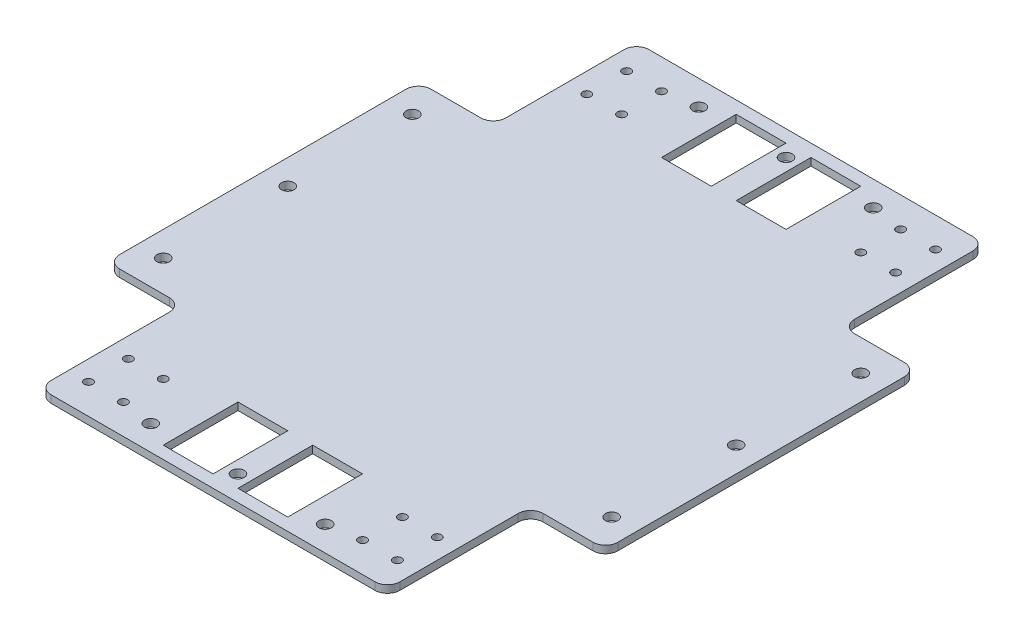
SolidWorks part; units mm, degrees
ref_plane "前视基准面" through (0, 0, 0) normal (0, 0, 1) x (1, 0, 0)
ref_plane "上视基准面" through (0, 0, 0) normal (0, 1, 0) x (1, 0, 0)
ref_plane "右视基准面" through (0, 0, 0) normal (1, 0, 0) x (0, 0, -1)
other "Configuration Table"
sketch "草图1" plane through (0, 0, 0) normal (0, 1, 0) x (1, 0, 0)
  line L0 (0, 120) -> (0, -49880) construction
  line L5 (-100, -120) -> (100, 120) construction
  line L6 (-100, 120) -> (100, -120) construction
  line L7 (-100, 120) -> (-70, 120)
  line L8 (-100, 120) -> (-100, 80)
  line L9 (-95, 80) -> (-75, 80)
  line L10 (-70, 115) -> (-70, 85)
  line L11 (-65, 0) -> (49935, 0) construction
  line L12 (-70, 120) -> (-70, 113)
  line L13 (-70, 113) -> (-70, 87)
  line L14 (-70, 87) -> (-70, 80)
  line L15 (-70, 113) -> (-40, 113)
  line L16 (-40, 113) -> (-40, 87)
  line L17 (-40, 87) -> (-70, 87)
  line L18 (-70, 113) -> (-70, 108)
  line L19 (-70, 87) -> (-70, 92)
  line L20 (-40, 87) -> (-48, 87)
  line L21 (-48, 87) -> (-48, 92)
  line L22 (-48, 92) -> (-40, 92)
  line L23 (-70, 92) -> (-62, 92)
  line L24 (-62, 92) -> (-62, 87)
  line L25 (-70, 100) -> (-40, 100) construction
  line L26 (0, 120) -> (0, 0)
  line L27 (0, 0) -> (-100, 0)
  line L28 (-70, 80) -> (0, 80)
  line L29 (95, 80) -> (75, 80)
  line L30 (70, 115) -> (70, 85)
  line L31 (95, -80) -> (75, -80)
  line L32 (70, -115) -> (70, -85)
  line L33 (-70, -115) -> (-70, -85)
  line L34 (-95, -80) -> (-75, -80)
  line L35 (0, 120) -> (0, 100)
  line L36 (0, 100) -> (-25, 100)
  line L37 (-25, 100) -> (-25, 115)
  line L38 (-25, 100) -> (-25, 85)
  line L39 (-25, 85) -> (-5, 85)
  line L40 (-25, 115) -> (-5, 115)
  line L41 (-5, 115) -> (-5, 85)
  line L42 (5, 115) -> (5, 85)
  line L43 (25, 100) -> (25, 85)
  line L44 (25, 85) -> (5, 85)
  line L45 (25, 115) -> (5, 115)
  line L46 (25, 100) -> (25, 115)
  line L47 (25, -85) -> (5, -85)
  line L48 (25, -100) -> (25, -85)
  line L49 (25, -100) -> (25, -115)
  line L50 (25, -115) -> (5, -115)
  line L51 (5, -115) -> (5, -85)
  line L52 (-25, -100) -> (-25, -115)
  line L53 (-25, -100) -> (-25, -85)
  line L54 (-25, -85) -> (-5, -85)
  line L55 (-5, -115) -> (-5, -85)
  line L56 (-25, -115) -> (-5, -115)
  line L57 (-100, 0) -> (-90, 0)
  line L58 (0, 120) -> (0, 100)
  line L59 (0, 120) -> (0, 110)
  line L60 (-100, 75) -> (-100, -75)
  line L61 (-65, -120) -> (65, -120)
  line L62 (100, 75) -> (100, -75)
  line L63 (-65, 120) -> (65, 120)
  circle A0 centre (-62, 92) radius 1.7
  circle A1 centre (-48, 92) radius 1.7
  circle A2 centre (-48, 108) radius 1.7
  circle A3 centre (-62, 108) radius 1.7
  circle A4 centre (48, 108) radius 1.7
  circle A5 centre (48, 92) radius 1.7
  circle A6 centre (62, 92) radius 1.7
  circle A7 centre (62, 108) radius 1.7
  circle A8 centre (62, -108) radius 1.7
  circle A9 centre (62, -92) radius 1.7
  circle A10 centre (48, -92) radius 1.7
  circle A11 centre (48, -108) radius 1.7
  circle A12 centre (-48, -92) radius 1.7
  circle A13 centre (-62, -92) radius 1.7
  circle A14 centre (-48, -108) radius 1.7
  circle A15 centre (-62, -108) radius 1.7
  circle A16 centre (-90, 0) radius 2.5
  circle A17 centre (-90, 50) radius 2.5
  circle A18 centre (-90, -50) radius 2.5
  circle A19 centre (90, -50) radius 2.5
  circle A20 centre (90, 0) radius 2.5
  circle A21 centre (90, 50) radius 2.5
  circle A22 centre (0, 110) radius 2.5
  circle A23 centre (35, 110) radius 2.5
  circle A24 centre (-35, 110) radius 2.5
  circle A25 centre (35, -110) radius 2.5
  circle A26 centre (0, -110) radius 2.5
  circle A27 centre (-35, -110) radius 2.5
  arc A28 (-95, -80) -> (-100, -75) centre (-95, -75) cw
  arc A29 (-70, -85) -> (-75, -80) centre (-75, -85) ccw
  arc A30 (-65, -120) -> (-70, -115) centre (-65, -115) cw
  arc A31 (70, -115) -> (65, -120) centre (65, -115) cw
  arc A32 (70, 85) -> (75, 80) centre (75, 85) ccw
  arc A33 (75, -80) -> (70, -85) centre (75, -85) ccw
  arc A34 (95, -80) -> (100, -75) centre (95, -75) ccw
  arc A35 (95, 80) -> (100, 75) centre (95, 75) cw
  arc A36 (70, 115) -> (65, 120) centre (65, 115) ccw
  arc A37 (-70, 115) -> (-65, 120) centre (-65, 115) cw
  arc A38 (-70, 85) -> (-75, 80) centre (-75, 85) cw
  arc A39 (-95, 80) -> (-100, 75) centre (-95, 75) ccw
  point P0 (0, 0)
  point P15 (-100, -80)
  point P119 (-70, -80)
  point P122 (-70, -120)
  point P125 (70, -120)
  point P128 (70, 80)
  point P131 (70, -80)
  point P134 (100, -80)
  point P137 (100, 80)
  point P140 (70, 120)
  dimension "D12" = 3.4
  dimension "D13" = 3.4
  dimension "D19" = 5
  dimension "D23" = 5
  dimension "D25" = 5
  dimension "D26" = 5
  dimension "D1" = 200
  dimension "D2" = 240
  dimension "D3" = 30
  dimension "D4" = 40
  dimension "D5" = 7
  dimension "D6" = 7
  dimension "D7" = 30
  dimension "D8" = 5
  dimension "D9" = 5
  dimension "D10" = 8
  dimension "D11" = 8
  dimension "D14" = 25
  dimension "D15" = 15
  dimension "D16" = 15
  dimension "D17" = 20
  dimension "D18" = 10
  dimension "D21" = 20
  dimension "D22" = 10
  dimension "D20" = 2
  dimension "D24" = 2
extrude "凸台-拉伸2" add sketch "草图1" along normal blind 3
sketch "草图3" plane through (0, 3, 0) normal (0, 1, 0) x (1, 0, 0)
  line L0 (-100, 75) -> (-100, 57.5)
  line L1 (-70, 85) -> (-100, 85)
  line L2 (-70, 85) -> (-70, 75)
  line L3 (-70, 75) -> (-100, 75)
  line L4 (-100, 85) -> (-100, 75)
  line L5 (-100, 75) -> (-70, 75)
  line L6 (-100, 75) -> (-100, 62.5)
  line L7 (-95, 62.5) -> (-75, 62.5)
  line L8 (-70, 75) -> (-70, 67.5)
  line L9 (-100, 62.5) -> (-70, 62.5)
  line L10 (-100, 57.5) -> (-100, 55.3401)
  line L11 (-100, 55.3401) -> (-70, 55.3401)
  line L12 (-70, 62.5) -> (-70, 55.3401)
  line L13 (-70, 62.284) -> (-70, 67.5)
  line L14 (0, 0) -> (50000, 0) construction
  line L15 (0, -1000) -> (0, 49000) construction
  line L16 (-100, 62.5) -> (-100, 57.5)
  line L17 (-100, 62.5) -> (-100, 75)
  line L18 (100, 62.5) -> (100, 75)
  line L19 (100, 62.5) -> (100, 57.5)
  line L20 (70, 62.284) -> (70, 67.5)
  line L21 (70, 62.5) -> (70, 55.3401)
  line L22 (100, 55.3401) -> (70, 55.3401)
  line L23 (100, 57.5) -> (100, 55.3401)
  line L24 (100, 62.5) -> (70, 62.5)
  line L25 (70, 75) -> (70, 67.5)
  line L26 (95, 62.5) -> (75, 62.5)
  line L27 (100, 75) -> (100, 62.5)
  line L28 (100, 75) -> (70, 75)
  line L29 (100, 85) -> (100, 75)
  line L30 (70, 75) -> (100, 75)
  line L31 (70, 85) -> (70, 75)
  line L32 (70, 85) -> (100, 85)
  line L33 (100, 75) -> (100, 57.5)
  line L34 (100, -75) -> (100, -57.5)
  line L35 (70, -85) -> (100, -85)
  line L36 (70, -85) -> (70, -75)
  line L37 (70, -75) -> (100, -75)
  line L38 (100, -85) -> (100, -75)
  line L39 (100, -75) -> (70, -75)
  line L40 (100, -75) -> (100, -62.5)
  line L41 (95, -62.5) -> (75, -62.5)
  line L42 (70, -75) -> (70, -67.5)
  line L43 (100, -62.5) -> (70, -62.5)
  line L44 (100, -57.5) -> (100, -55.3401)
  line L45 (100, -55.3401) -> (70, -55.3401)
  line L46 (70, -62.5) -> (70, -55.3401)
  line L47 (70, -62.284) -> (70, -67.5)
  line L48 (100, -62.5) -> (100, -57.5)
  line L49 (100, -62.5) -> (100, -75)
  line L50 (-100, -62.5) -> (-100, -75)
  line L51 (-100, -62.5) -> (-100, -57.5)
  line L52 (-70, -62.284) -> (-70, -67.5)
  line L53 (-70, -62.5) -> (-70, -55.3401)
  line L54 (-100, -55.3401) -> (-70, -55.3401)
  line L55 (-100, -57.5) -> (-100, -55.3401)
  line L56 (-100, -62.5) -> (-70, -62.5)
  line L57 (-70, -75) -> (-70, -67.5)
  line L58 (-95, -62.5) -> (-75, -62.5)
  line L59 (-100, -75) -> (-100, -62.5)
  line L60 (-100, -75) -> (-70, -75)
  line L61 (-100, -85) -> (-100, -75)
  line L62 (-70, -75) -> (-100, -75)
  line L63 (-70, -85) -> (-70, -75)
  line L64 (-70, -85) -> (-100, -85)
  line L65 (-100, -75) -> (-100, -57.5)
  arc A0 (-75, 62.5) -> (-70, 67.5) centre (-75, 67.5) ccw
  arc A1 (-95, 62.5) -> (-100, 57.5) centre (-95, 57.5) ccw
  arc A2 (95, 62.5) -> (100, 57.5) centre (95, 57.5) cw
  arc A3 (75, 62.5) -> (70, 67.5) centre (75, 67.5) cw
  arc A4 (75, -62.5) -> (70, -67.5) centre (75, -67.5) ccw
  arc A5 (95, -62.5) -> (100, -57.5) centre (95, -57.5) ccw
  arc A6 (-95, -62.5) -> (-100, -57.5) centre (-95, -57.5) cw
  arc A7 (-75, -62.5) -> (-70, -67.5) centre (-75, -67.5) cw
  dimension "D2" = 5
  dimension "D1" = 12.5
extrude "切除-拉伸2" cut sketch "草图3" against normal blind 3 contours L32 L31 L28 L29 | A3 L24 L18 L28 L25 | L24 A2 L19 | L1 L4 L3 L2 | L7 A0 L8 L3 L0 L9 | A1 L9 L0 | A7 L56 L50 L60 L57 | L64 L63 L60 L61 | L56 A6 L51 | L35 L38 L37 L36 | L41 A4 L42 L37 L34 L43 | A5 L43 L34
